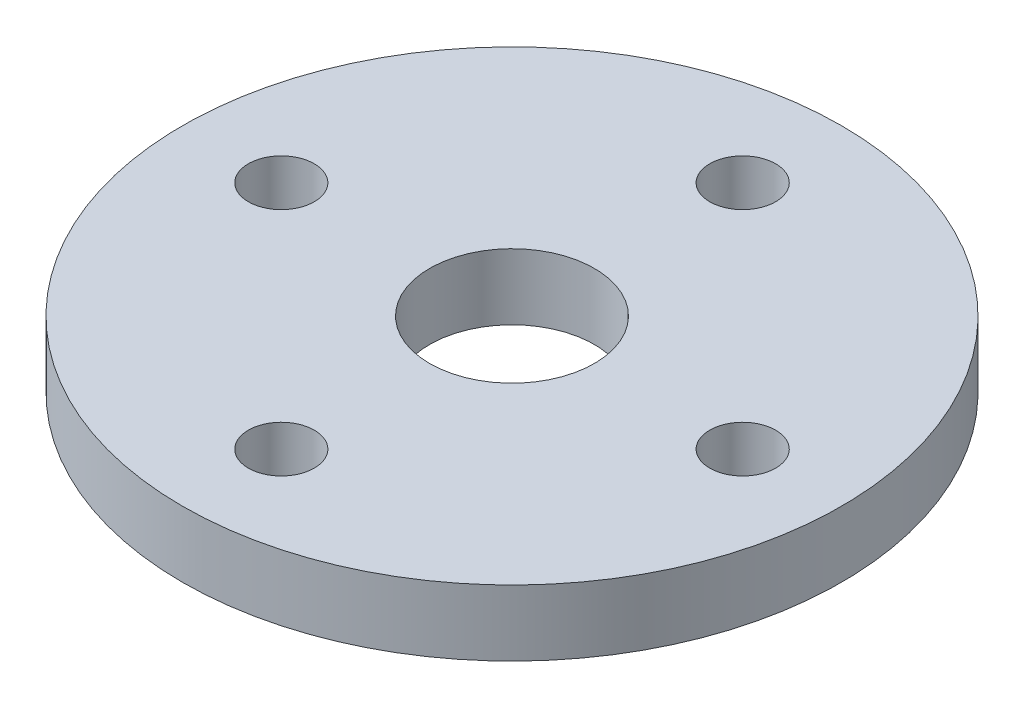
SolidWorks part; units mm, degrees
ref_plane "Front Plane" through (0, 0, 0) normal (0, 0, 1) x (1, 0, 0)
ref_plane "Top Plane" through (0, 0, 0) normal (0, 1, 0) x (1, 0, 0)
ref_plane "Right Plane" through (0, 0, 0) normal (1, 0, 0) x (0, 0, -1)
sketch "Sketch1" plane through (0, 0, 0) normal (0, 1, 0) x (1, 0, 0)
  circle A0 centre (0, 0) radius 10
extrude "Boss-Extrude1" add sketch "Sketch1" along normal blind 2
sketch "Sketch2" plane through (0, 2, 0) normal (0, 1, 0) x (1, 0, 0)
  circle A0 centre (0, 0) radius 2.5
extrude "Cut-Extrude1" cut sketch "Sketch2" against normal blind 2
sketch "Sketch3" plane through (0, 2, 0) normal (0, 1, 0) x (1, 0, 0)
  circle A0 centre (7, 0) radius 1
  circle A1 centre (0, -7) radius 1
  circle A2 centre (-7, 0) radius 1
  circle A3 centre (0, 7) radius 1
  point P12 (0, 0)
  dimension "D1" = 7
  dimension "D2" = 4
extrude "Cut-Extrude2" cut sketch "Sketch3" against normal blind 2
